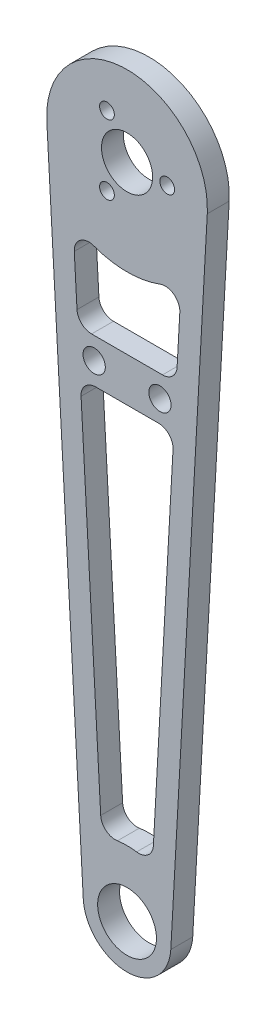
SolidWorks part; units mm, degrees
material "Thornel Mat VMA"
ref_plane "前视基准面" through (0, 0, 0) normal (0, 0, 1) x (1, 0, 0)
ref_plane "上视基准面" through (0, 0, 0) normal (0, 1, 0) x (1, 0, 0)
ref_plane "右视基准面" through (0, 0, 0) normal (1, 0, 0) x (0, 0, -1)
sketch "草图1" plane through (0, 0, 0) normal (0, 0, 1) x (1, 0, 0)
  line L0 (0, 0) -> (0, -90) construction
  line L1 (-10.983, -0.6111) -> (-5.9907, -90.3333)
  line L2 (10.983, -0.6111) -> (5.9907, -90.3333)
  line L3 (-7.4184, -10.6756) -> (-3.4668, -81.6945)
  line L4 (7.4184, -10.6756) -> (3.4668, -81.6945)
  circle A0 centre (0, 0) radius 11
  circle A1 centre (0, -90) radius 6
  circle A2 centre (0, 0) radius 5.5 construction
  circle A3 centre (5.5, 0) radius 1.01
  circle A4 centre (-2.75, -4.7631) radius 1.01
  circle A5 centre (-2.75, 4.7631) radius 1.01
  circle A6 centre (0, 0) radius 3.5
  circle A7 centre (0, -90) radius 4.025
  arc A8 (-7.4184, -10.6756) -> (7.4184, -10.6756) centre (0, 0) ccw
  arc A10 (3.4668, -81.6945) -> (-3.4668, -81.6945) centre (0, -90) ccw
  point P14 (0, 0)
  dimension "D1" = 22
  dimension "D2" = 11
  dimension "D3" = 2.02
  dimension "D5" = 7
  dimension "D6" = 12
  dimension "D7" = 8.05
  dimension "D10" = 2
  dimension "D11" = 9
  dimension "D8" = 90
  dimension "D9" = 3
  dimension "D4" = 3
extrude "凸台-拉伸1" add sketch "草图1" along normal blind 3 contours A1 L2 A0 L1 L4 A10 L3 A8 | A0 A6 A5 A4 A3 | A1 A7
sketch "草图2" plane through (0, 0, 3) normal (0, 0, 1) x (1, 0, 0)
  line L0 (-6.7452, -22.7747) -> (6.7452, -22.7747)
  line L1 (-7.4184, -10.6756) -> (-3.4668, -81.6945) construction
  line L2 (7.4184, -10.6756) -> (3.4668, -81.6945) construction
  line L3 (-6.4113, -28.7747) -> (6.4113, -28.7747)
  line L4 (0, 0) -> (0, -50000) construction
  line L5 (-6.7452, -22.7747) -> (-6.4113, -28.7747)
  line L6 (6.7452, -22.7747) -> (6.4113, -28.7747)
  circle A0 centre (-4.5, -25.7747) radius 1.525
  circle A2 centre (4.5, -25.7747) radius 1.525
  dimension "D1" = 3.05
  dimension "D3" = 3
  dimension "D2" = 9
  dimension "D4" = 3
extrude "凸台-拉伸2" add sketch "草图2" against normal up to surface (3 mm away) up to face at (0, -43.9861, 0)
fillet "圆角1" radius 2 8 edges at (-7.4184, -10.6756, 1.5) (-3.4668, -81.6945, 1.5) (3.4668, -81.6945, 1.5) (7.4184, -10.6756, 1.5) (6.7452, -22.7747, 1.5) (-6.4113, -28.7747, 1.5) (6.4113, -28.7747, 1.5) (-6.7452, -22.7747, 1.5)
